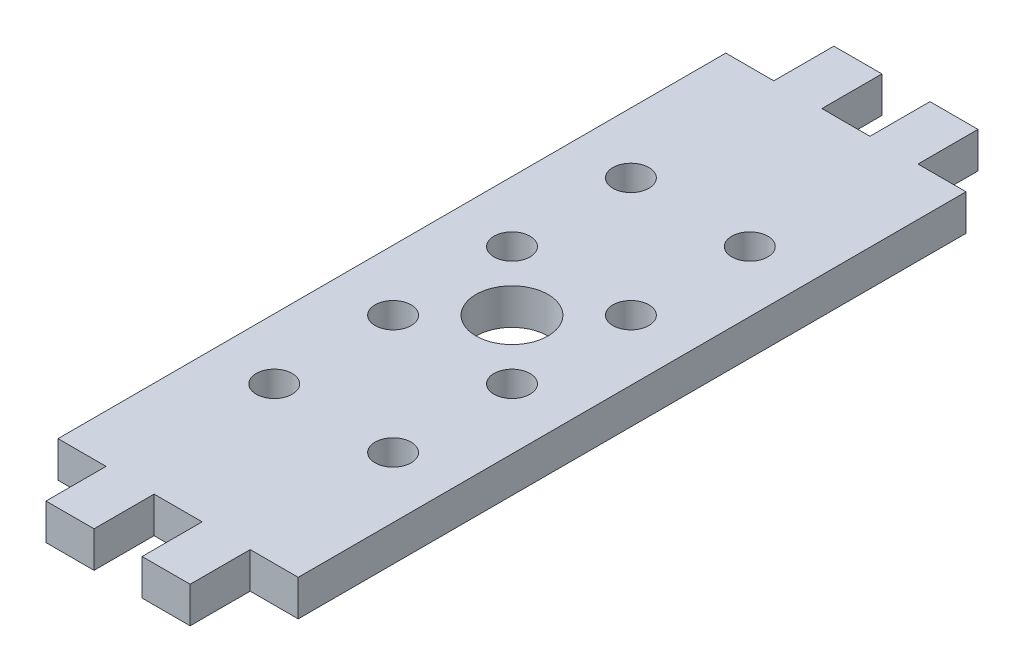
SolidWorks part; units mm, degrees
material "PF"
ref_plane "前视基准面" through (0, 0, 0) normal (0, 0, 1) x (1, 0, 0)
ref_plane "上视基准面" through (0, 0, 0) normal (0, 1, 0) x (1, 0, 0)
ref_plane "右视基准面" through (0, 0, 0) normal (1, 0, 0) x (0, 0, -1)
sketch "草图1" plane through (0, 0, 0) normal (0, 1, 0) x (1, 0, 0)
  line L1 (-20, 0) -> (0, 0)
  line L2 (-20, 0) -> (-20, -55.6)
  line L3 (-20, -55.6) -> (0, -55.6)
  line L4 (0, 0) -> (0, -55.6)
  dimension "D1" = 20
  dimension "D2" = 55.6
extrude "凸台-拉伸1" add sketch "草图1" along normal blind 3
sketch "草图2" plane through (0, 3, 0) normal (0, 1, 0) x (1, 0, 0)
  line L0 (0, -27.8) -> (-20, -27.8) construction
  line L1 (0, -55.6) -> (0, 0) construction
  line L2 (-20, 0) -> (-20, -55.6) construction
  line L3 (-8, 0) -> (-12, 0)
  line L4 (0, 0) -> (-20, 0) construction
  line L5 (-8, 0) -> (-4, 0)
  line L6 (-8, 0) -> (-8, 5)
  line L7 (-4, 0) -> (-4, 5)
  line L8 (-8, 5) -> (-4, 5)
  line L9 (-10, -27.8) -> (-10, 0) construction
  line L10 (-16, 0) -> (-16, 5)
  line L11 (-12, 5) -> (-16, 5)
  line L12 (-12, 0) -> (-12, 5)
  line L13 (-12, 0) -> (-16, 0)
  line L14 (-12, -55.6) -> (-16, -55.6)
  line L15 (-12, -55.6) -> (-12, -60.6)
  line L16 (-12, -60.6) -> (-16, -60.6)
  line L17 (-16, -55.6) -> (-16, -60.6)
  line L18 (-4, -55.6) -> (-4, -60.6)
  line L19 (-8, -60.6) -> (-4, -60.6)
  line L20 (-8, -55.6) -> (-8, -60.6)
  line L21 (-8, -55.6) -> (-4, -55.6)
  point P11 (-10, 0)
  line M13 (-20, -55.6) -> (0, -55.6)
  line M15 (0, 0) -> (-20, 0)
  dimension "D1" = 4
  dimension "D2" = 5
  dimension "D3" = 4
extrude "凸台-拉伸2" add sketch "草图2" against normal blind 3 contours L8 L6 L7 M15 | L3 L12 L11 L10 M15 | L20 L19 L18 M13 | L17 L16 L15 M13
sketch "草图3" plane through (0, 3, 0) normal (0, 1, 0) x (1, 0, 0)
  line L0 (0, -27.8) -> (-20, -27.8) construction
  line L1 (0, -55.6) -> (0, 0) construction
  line L2 (-20, 0) -> (-20, -55.6) construction
  line L3 (-14.9497, -32.7497) -> (-5.0503, -22.8503)
  line L4 (-5.0503, -22.8503) -> (-14.9497, -22.8503) construction
  circle A0 centre (-10, -27.8) radius 3
  circle A1 centre (-5.0503, -22.8503) radius 1.5
  circle A2 centre (-5.0503, -32.7497) radius 1.5
  circle A3 centre (-14.9497, -32.7497) radius 1.5
  circle A4 centre (-14.9497, -22.8503) radius 1.5
  circle A5 centre (-14.9497, -12.9508) radius 1.5
  circle A6 centre (-5.0503, -12.9508) radius 1.5
  circle A7 centre (-14.9497, -42.6492) radius 1.5
  circle A8 centre (-5.0503, -42.6492) radius 1.5
  point P11 (-10, -27.8)
  dimension "D1" = 4
extrude "切除-拉伸1" cut sketch "草图3" against normal blind 10
